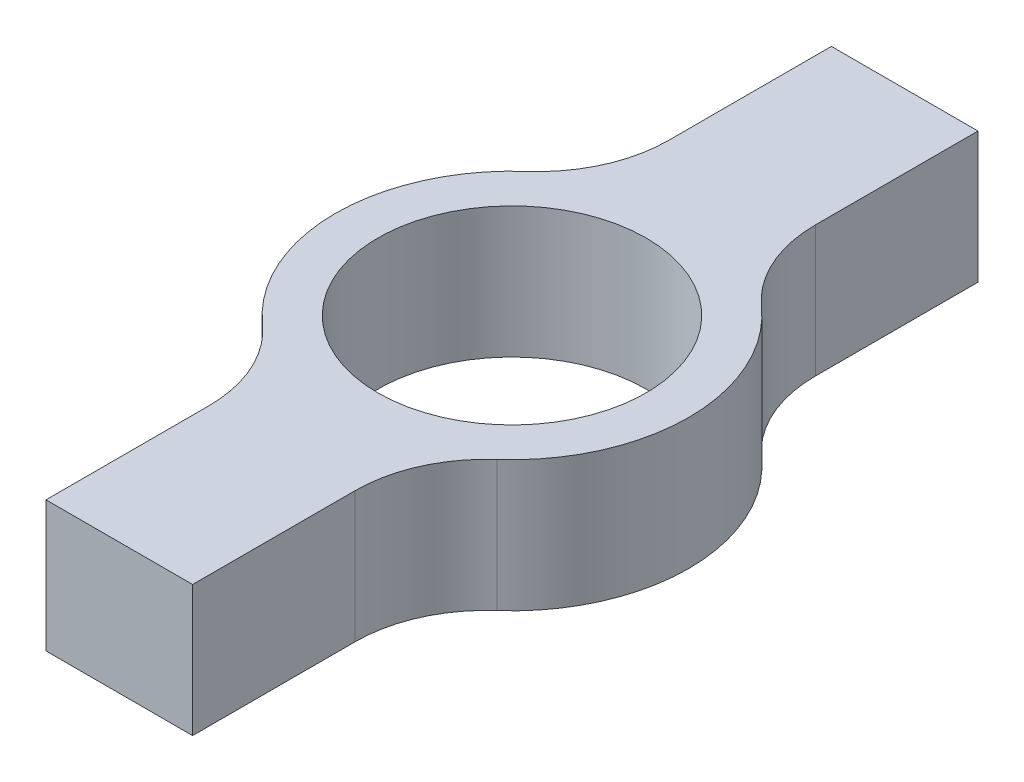
SolidWorks part; units mm, degrees
ref_plane "前视基准面" through (0, 0, 0) normal (0, 0, 1) x (1, 0, 0)
ref_plane "上视基准面" through (0, 0, 0) normal (0, 1, 0) x (1, 0, 0)
ref_plane "右视基准面" through (0, 0, 0) normal (1, 0, 0) x (0, 0, -1)
other "Configuration Table"
sketch "草图1" plane through (0, 0, 0) normal (0, 1, 0) x (1, 0, 0)
  circle A0 centre (0, 0) radius 13.5
  dimension "D1" = 27
extrude "凸台-拉伸1" add sketch "草图1" along normal blind 10
sketch "草图2" plane through (0, 10, 0) normal (0, 1, 0) x (1, 0, 0)
  line L0 (0, 0) -> (0, 13.5) construction
  line L1 (0, 0) -> (0, -13.5) construction
  line L3 (-5.6, 30) -> (5.6, 30)
  line L4 (-5.6, 30) -> (-5.6, -30)
  line L5 (-5.6, -30) -> (5.6, -30)
  line L6 (5.6, 30) -> (5.6, -30)
  circle A0 centre (0, 0) radius 13.5 construction
  dimension "D1" = 11.2
  dimension "D2" = 5.6
  dimension "D3" = 60
  dimension "D4" = 30
extrude "凸台-拉伸2" add sketch "草图2" against normal blind 10
sketch "草图3" plane through (0, 10, 0) normal (0, 1, 0) x (1, 0, 0)
  circle A0 centre (0, 0) radius 10.25
  dimension "D1" = 20.5
extrude "切除-拉伸1" cut sketch "草图3" against normal blind 10
fillet "圆角1" radius 10 4 edges at (5.6, 5, 12.2837) (5.6, 5, -12.2837) (-5.6, 5, -12.2837) (-5.6, 5, 12.2837)
